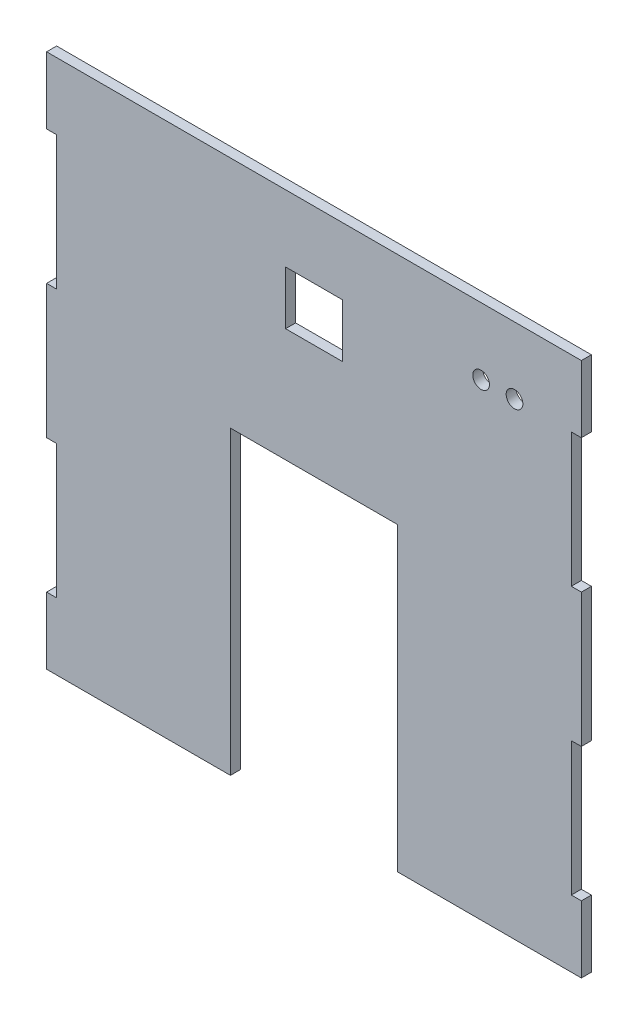
SolidWorks part; units mm, degrees
ref_plane "Front Plane" through (0, 0, 0) normal (0, 0, 1) x (1, 0, 0)
ref_plane "Top Plane" through (0, 0, 0) normal (0, 1, 0) x (1, 0, 0)
ref_plane "Right Plane" through (0, 0, 0) normal (1, 0, 0) x (0, 0, -1)
sketch "Sketch1" plane through (0, 0, 0) normal (0, 0, 1) x (1, 0, 0)
  line L0 (0, 10) -> (0, 80) construction
  line L1 (-80, 80) -> (80, 80)
  line L2 (-80, 80) -> (-80, -80)
  line L3 (-80, -80) -> (80, -80)
  line L4 (80, 80) -> (80, -80)
  line L5 (-80, 80) -> (80, -80) construction
  line L6 (-80, -80) -> (80, 80) construction
  line L7 (-25, -80) -> (25, -80)
  line L8 (-25, -80) -> (-25, 10)
  line L9 (-25, 10) -> (25, 10)
  line L10 (25, -80) -> (25, 10)
  line L11 (80, 60) -> (-80, 60) construction
  line L12 (0, 80) -> (0, 60) construction
  line L13 (-8.5, 60) -> (8.5, 60)
  line L14 (-8.5, 60) -> (-8.5, 44)
  line L15 (-8.5, 44) -> (8.5, 44)
  line L16 (8.5, 60) -> (8.5, 44)
  circle A0 centre (50, 60) radius 2.5
  circle A1 centre (60, 60) radius 2.5
  point P0 (0, 0)
  dimension "D6" = 5
  dimension "D1" = 160
  dimension "D2" = 160
  dimension "D3" = 90
  dimension "D4" = 50
  dimension "D5" = 20
  dimension "D7" = 10
  dimension "D8" = 20
  dimension "D9" = 17
  dimension "D10" = 16
extrude "Boss-Extrude1" add sketch "Sketch1" along normal blind 3 contours L10 L3 L4 L1 L2 L8 L9 A1 A0 L13 L16 L15 L14
sketch "Sketch2" plane through (0, 0, 3) normal (0, 0, 1) x (1, 0, 0)
  line L0 (-80, -60) -> (-77, -60)
  line L1 (-80, 80) -> (-80, -80) construction
  line L2 (-77, -60) -> (-77, -20)
  line L3 (-77, -20) -> (-80, -20)
  line L4 (-80, -20) -> (-80, 20)
  line L5 (-80, 20) -> (-77, 20)
  line L6 (-77, 20) -> (-77, 60)
  line L7 (-77, 60) -> (-80, 60)
  line L8 (-80, 60) -> (-80, -60)
  line L9 (-77, 20) -> (-77, -20) construction
  line L10 (-77, 0) -> (80, 0) construction
  line L11 (80, 80) -> (80, -80) construction
  line L12 (80, 60) -> (77, 60)
  line L13 (77, 60) -> (77, 20)
  line L14 (77, 20) -> (80, 20)
  line L15 (80, 20) -> (80, -20)
  line L16 (80, -20) -> (77, -20)
  line L17 (77, -20) -> (77, -60)
  line L18 (77, -60) -> (80, -60)
  line L19 (80, -60) -> (80, 60)
  line L20 (77, 20) -> (77, -20) construction
  line L21 (77, 0) -> (-80, 0) construction
  line M21 (80, -80) -> (80, 80)
  line M23 (-80, 80) -> (-80, -80)
  dimension "D1" = 40
  dimension "D2" = 40
  dimension "D3" = 3
  dimension "D4" = 40
  dimension "D5" = 3
  dimension "D6" = 40
extrude "Cut-Extrude1" cut sketch "Sketch2" against normal through all contours L6 L7 L5 M23 | L2 L3 L0 M23 | L17 L18 L16 M21 | L13 L14 L12 M21
